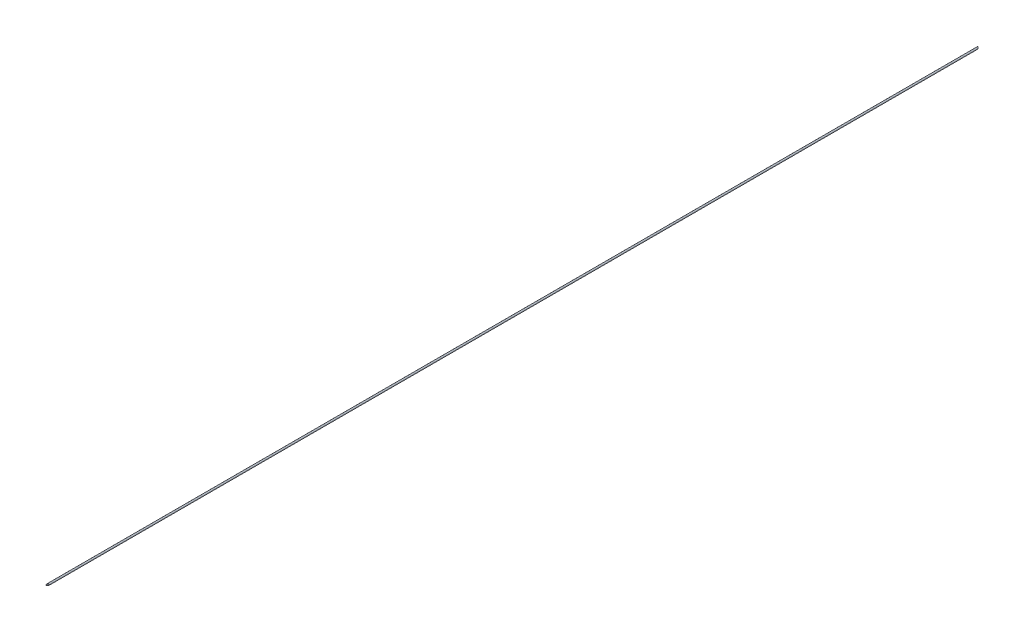
SolidWorks part; units mm, degrees
material "AISI 1015 Aço, trefilado (SS)"
ref_plane "Plano frontal" through (0, 0, 0) normal (0, 0, 1) x (1, 0, 0)
ref_plane "Plano superior" through (0, 0, 0) normal (0, 1, 0) x (1, 0, 0)
ref_plane "Plano direito" through (0, 0, 0) normal (1, 0, 0) x (0, 0, -1)
sketch "Esboço1" plane through (0, 0, 0) normal (0, 0, 1) x (1, 0, 0)
  circle A0 centre (0, 0) radius 5
  dimension "D1" = 10
extrude "Ressalto-extrusão1" add sketch "Esboço1" along normal mid plane 5560 contours A0
sketch "Esboço2" plane through (0, 0, 0) normal (0, 1, 0) x (1, 0, 0)
  line L0 (-5, -2780) -> (5, -2780) construction
  line L1 (-5, -2780) -> (5, -2780)
  line L2 (-5, -2780) -> (5, -2770)
  line L3 (5, -2780) -> (5, 2780) construction
  line L4 (5, -2770) -> (5, -2780)
  dimension "D1" = 45
extrude "Corte-extrusão1" cut sketch "Esboço2" against normal mid plane 10
mirror "Espelhar1" about plane through (0, 0, 0) normal (0, 0, 1) of "Corte-extrusão1"
